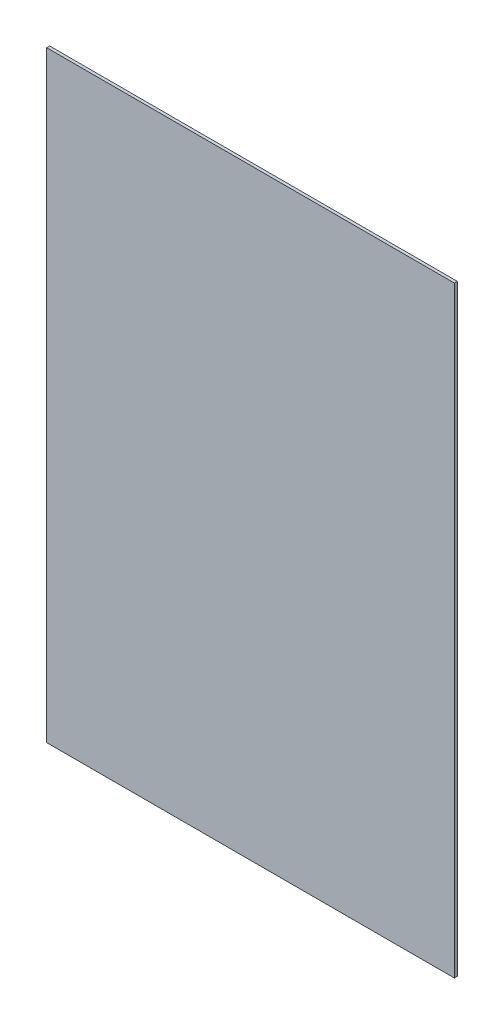
SolidWorks part; units mm, degrees
ref_plane "Front Plane" through (0, 0, 0) normal (0, 0, 1) x (1, 0, 0)
ref_plane "Top Plane" through (0, 0, 0) normal (0, 1, 0) x (1, 0, 0)
ref_plane "Right Plane" through (0, 0, 0) normal (1, 0, 0) x (0, 0, -1)
sketch "Sketch2" plane through (0, 0, 0) normal (0, 0, 1) x (1, 0, 0)
  line L1 (-657.9963, 410.9276) -> (722.0037, 410.9276)
  line L2 (-657.9963, 410.9276) -> (-657.9963, -1626.7724)
  line L3 (-657.9963, -1626.7724) -> (722.0037, -1626.7724)
  line L4 (722.0037, 410.9276) -> (722.0037, -1626.7724)
  dimension "D1" = 1380
  dimension "D2" = 2037.7
extrude "Boss-Extrude2" add sketch "Sketch2" along normal blind 10
